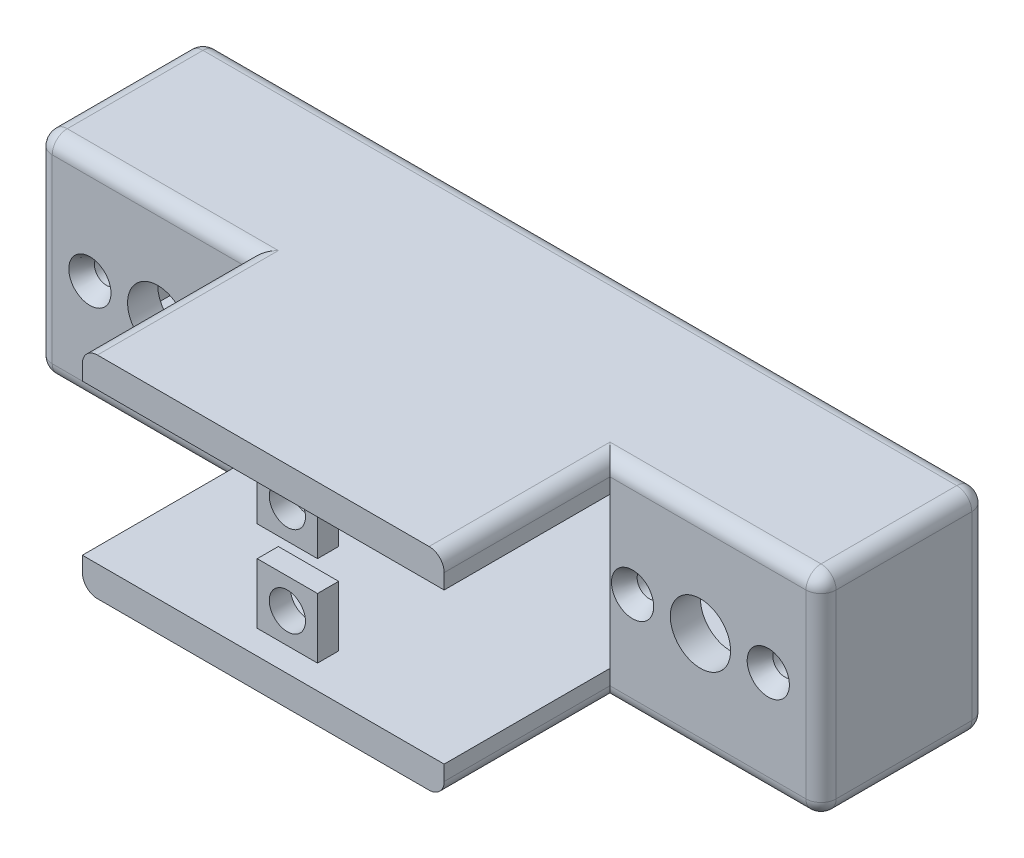
SolidWorks part; units mm, degrees
ref_plane "Front Plane" through (0, 0, 0) normal (0, 0, 1) x (1, 0, 0)
ref_plane "Top Plane" through (0, 0, 0) normal (0, 1, 0) x (1, 0, 0)
ref_plane "Right Plane" through (0, 0, 0) normal (1, 0, 0) x (0, 0, -1)
sketch "草图1" plane through (0, 0, 0) normal (0, 0, 1) x (1, 0, 0)
  line L1 (0, 0) -> (52, 0)
  line L2 (0, 0) -> (0, 14)
  line L3 (0, 14) -> (52, 14)
  line L4 (52, 0) -> (52, 14)
extrude "凸台-拉伸1" add sketch "草图1" along normal blind 11
shell "抽壳1" thickness 2
sketch "草图2" plane through (0, 0, 9) normal (0, 0, -1) x (-1, 0, 0)
  line L1 (-14, 12) -> (-38, 12)
  line L2 (-14, 12) -> (-14, 2)
  line L3 (-14, 2) -> (-38, 2)
  line L4 (-38, 12) -> (-38, 2)
extrude "切除-拉伸1" cut sketch "草图2" against normal blind 2
sketch "草图3" plane through (0, 0, 11) normal (0, 0, 1) x (1, 0, 0)
  line L0 (52, 14) -> (0, 14) construction
  line L1 (38, 2) -> (14, 2)
  line L2 (38, 2) -> (38, 0)
  line L3 (38, 0) -> (14, 0)
  line L4 (14, 2) -> (14, 0)
  line L5 (14, 12) -> (38, 12)
  line L6 (14, 12) -> (14, 14)
  line L7 (14, 14) -> (38, 14)
  line L8 (38, 12) -> (38, 14)
extrude "凸台-拉伸2" add sketch "草图3" along normal blind 11
sketch "草图8" plane through (0, 0, 11) normal (0, 0, 1) x (1, 0, 0)
  circle A0 centre (8, 7) radius 2
  circle A1 centre (44, 7) radius 2
extrude "切除-拉伸5" cut sketch "草图8" against normal blind 2
sketch "草图15" plane through (0, 0, 22) normal (0, 0, 1) x (1, 0, 0)
  line L1 (24, 2) -> (28, 2)
  line L2 (24, 2) -> (24, 6)
  line L3 (24, 6) -> (28, 6)
  line L4 (28, 2) -> (28, 6)
  line L5 (24, 8) -> (28, 8)
  line L6 (24, 8) -> (24, 12)
  line L7 (24, 12) -> (28, 12)
  line L8 (28, 8) -> (28, 12)
sketch "草图16" plane through (0, 0, 22) normal (0, 0, 1) x (1, 0, 0)
  circle A0 centre (26, 10) radius 1.2
  circle A1 centre (26, 4) radius 1.2
extrude "凸台-拉伸4" add sketch "草图15" against normal blind 3
sketch "草图17" plane through (0, 0, 22) normal (0, 0, 1) x (1, 0, 0)
  line L1 (38, 2) -> (14, 2)
  line L2 (38, 2) -> (38, 12)
  line L3 (38, 12) -> (14, 12)
  line L4 (14, 2) -> (14, 12)
ref_plane "基准面1" through (0, 7, 0) normal (0, 1, 0) x (1, 0, 0)
sketch "草图19" plane through (0, 7, 0) normal (0, 1, 0) x (1, 0, 0)
  line L0 (2.1, -11) -> (3.5, -11)
  line L3 (2.7, -9.9) -> (2.1, -11)
  line L4 (2.7, -9.9) -> (2.7, -9)
  line L5 (3.5, -11) -> (3.5, -9)
  line L6 (2.7, -9) -> (3.5, -9)
sketch "草图20" plane through (0, 7, 0) normal (0, 1, 0) x (1, 0, 0)
  line L0 (11.1, -11) -> (12.5, -11)
  line L1 (11.1, -11) -> (11.7, -9.9)
  line L2 (11.7, -9.9) -> (11.7, -9)
  line L3 (12.5, -11) -> (12.5, -9)
  line L4 (11.7, -9) -> (12.5, -9)
sketch "草图21" plane through (0, 7, 0) normal (0, 1, 0) x (1, 0, 0)
  line L0 (38.1, -11) -> (39.5, -11)
  line L1 (38.1, -11) -> (38.7, -9.9)
  line L2 (38.7, -9.9) -> (38.7, -9)
  line L3 (39.5, -11) -> (39.5, -9)
  line L4 (38.7, -9) -> (39.5, -9)
sketch "草图22" plane through (0, 7, 0) normal (0, 1, 0) x (1, 0, 0)
  line L0 (47.1, -11) -> (48.5, -11)
  line L1 (47.1, -11) -> (47.7, -9.9)
  line L2 (48.5, -11) -> (48.5, -9)
  line L3 (47.7, -9.9) -> (47.7, -9)
  line L4 (47.7, -9) -> (48.5, -9)
revolve "切除-旋转6" cut sketch "草图19" angle 360 about L5
revolve "切除-旋转7" cut sketch "草图20" angle 360 about L3
revolve "切除-旋转8" cut sketch "草图21" angle 360 about L3
revolve "切除-旋转9" cut sketch "草图22" angle 360 about L2
extrude "切除-拉伸10" cut sketch "草图16" against normal blind 10 contours A1 | A0
fillet "圆角1" radius 1 18 edges at (0, 14, 5.5) (0, 7, 11) (0, 0, 5.5) (0, 7, 0) (52, 0, 5.5) (52, 7, 11) (52, 14, 5.5) (52, 7, 0) (26, 14, 0) (14, 0, 16.5) (14, 14, 16.5) (38, 14, 16.5) (38, 0, 16.5) (45, 14, 11) (45, 0, 11) (7, 0, 11) (7, 14, 11) (26, 0, 0)
extrude "切除-拉伸11" cut sketch "草图17" against normal blind 1.6
